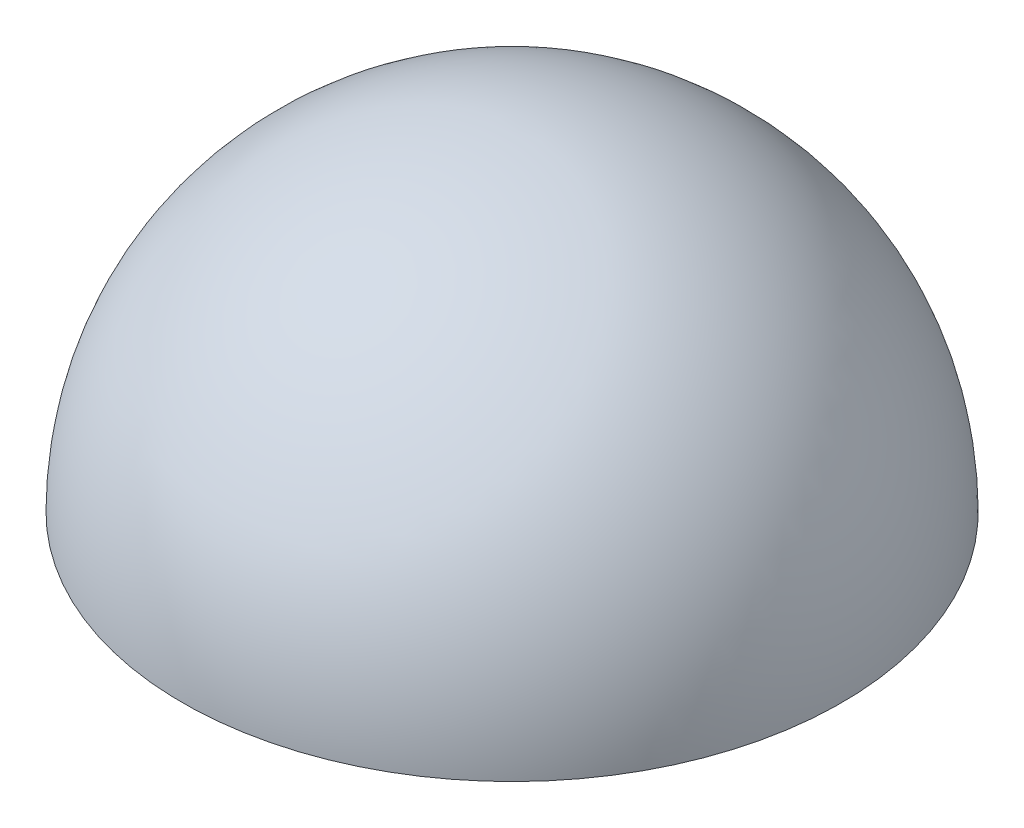
SolidWorks part; units mm, degrees
ref_plane "Front Plane" through (0, 0, 0) normal (0, 0, 1) x (1, 0, 0)
ref_plane "Top Plane" through (0, 0, 0) normal (0, 1, 0) x (1, 0, 0)
ref_plane "Right Plane" through (0, 0, 0) normal (1, 0, 0) x (0, 0, -1)
sketch "Sketch4" plane through (0, 0, 0) normal (0, 1, 0) x (1, 0, 0)
  line L0 (-9.525, 0) -> (9.525, 0)
  arc A0 (-9.525, 0) -> (9.525, 0) centre (0, 0) cw
  point P4 (0, 0)
  dimension "D1" = 19.05
revolve "Revolve1" add sketch "Sketch4" angle 180 about L0
